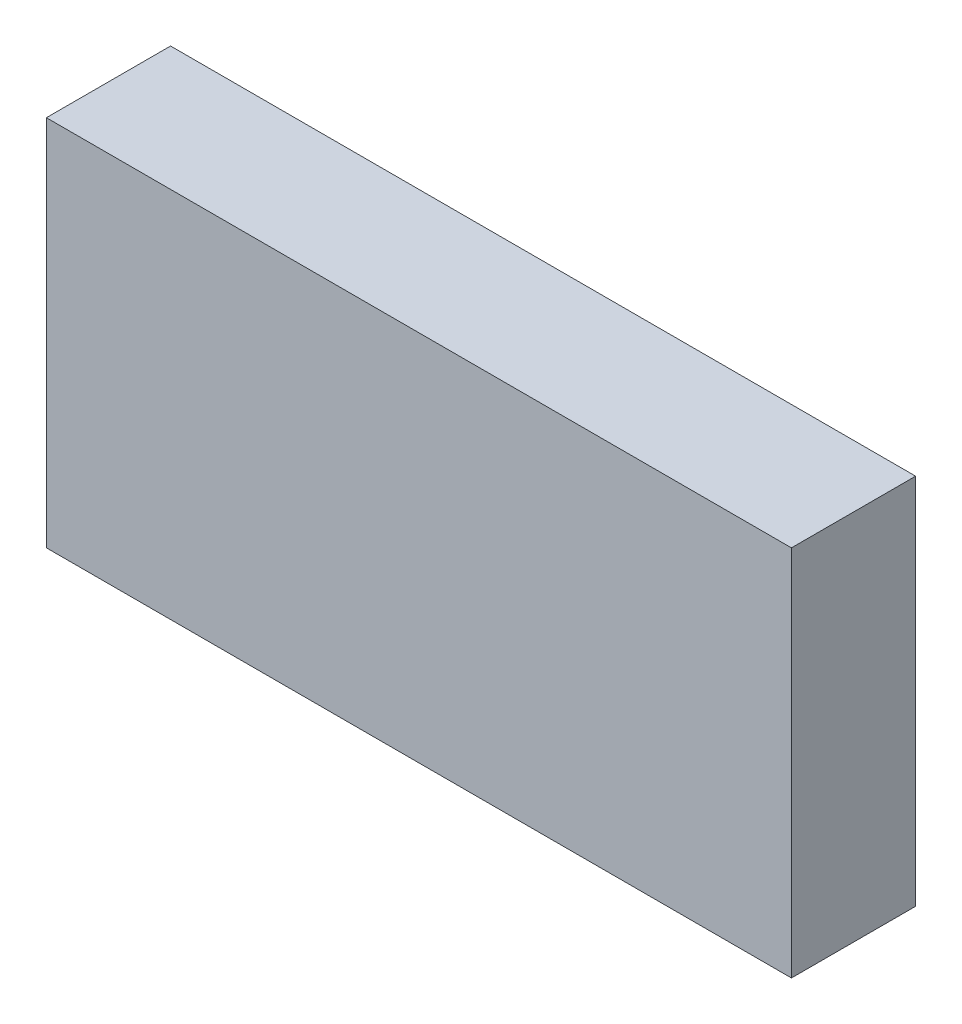
SolidWorks part; units mm, degrees
ref_plane "Front Plane" through (0, 0, 0) normal (0, 0, 1) x (1, 0, 0)
ref_plane "Top Plane" through (0, 0, 0) normal (0, 1, 0) x (1, 0, 0)
ref_plane "Right Plane" through (0, 0, 0) normal (1, 0, 0) x (0, 0, -1)
sketch "Sketch1" plane through (0, 0, 0) normal (0, 0, 1) x (1, 0, 0)
  line L1 (0, 0) -> (12, 0)
  line L2 (0, 0) -> (0, 6)
  line L3 (0, 6) -> (12, 6)
  line L4 (12, 0) -> (12, 6)
  dimension "D1" = 12
  dimension "D2" = 6
extrude "Profile" add sketch "Sketch1" along normal blind 2
equation "\"Profile_Depth\"= 2mm"
equation "\"D1@Profile\" = \"Profile_Depth\""
equation "\"Profile_Sketch_1\"= 12mm"
equation "\"D1@Sketch1\" = \"Profile_Sketch_1\""
equation "\"Profile_Sketch_2\"= 6mm"
equation "\"D2@Sketch1\" = \"Profile_Sketch_2\""
equation "\"EnvelopeWidth\"= 12mm"
equation "\"EnvelopeHeight\"= 6mm"
